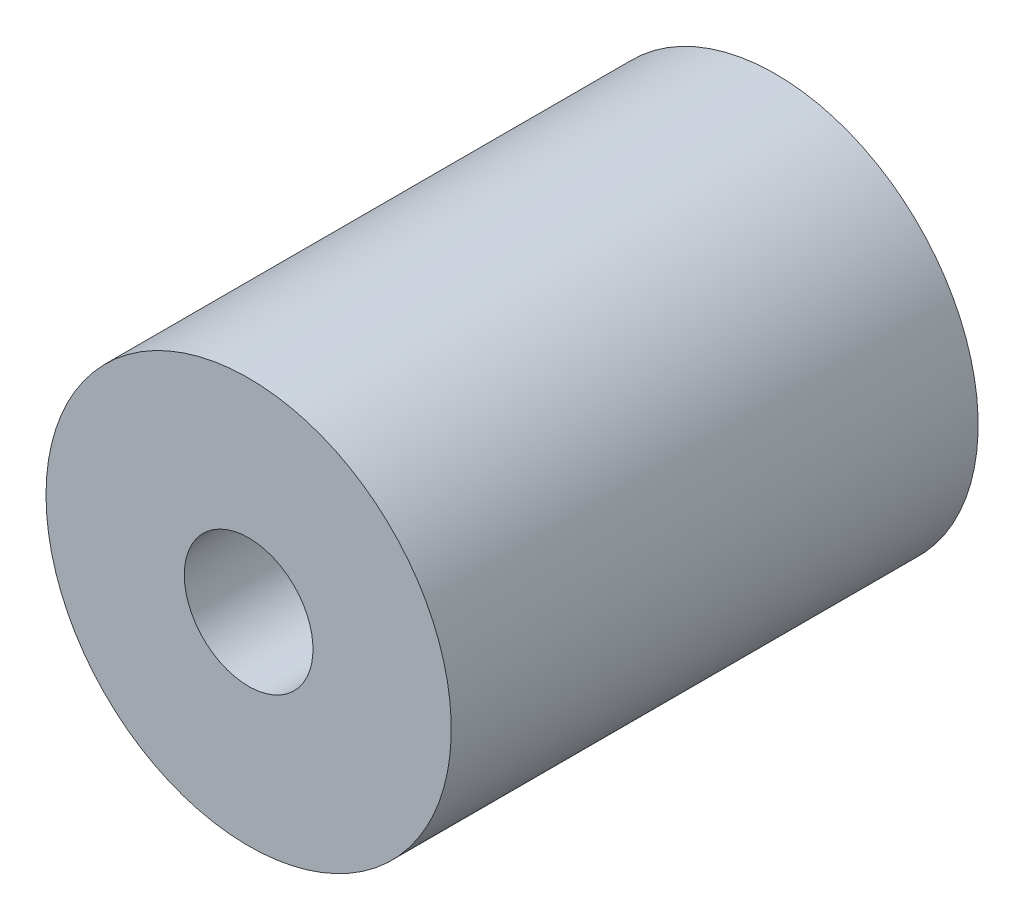
SolidWorks part; units mm, degrees
material "SKD11淬火HRC56-60"
ref_plane "前基準面" through (0, 0, 0) normal (0, 0, 1) x (1, 0, 0)
ref_plane "上基準面" through (0, 0, 0) normal (0, 1, 0) x (1, 0, 0)
ref_plane "右基準面" through (0, 0, 0) normal (1, 0, 0) x (0, 0, -1)
sketch "草图1" plane through (0, 0, 0) normal (0, 0, 1) x (1, 0, 0)
  circle A0 centre (0, 0) radius 10
  circle A1 centre (0, 0) radius 3.175
  dimension "D1" = 6.35
  dimension "D2" = 20
extrude "凸台-拉伸1" add sketch "草图1" along normal blind 26
sketch "草图3" plane through (0, 0, 0) normal (0, 0, -1) x (-1, 0, 0)
  circle A0 centre (0, 0) radius 4
  dimension "D1" = 8
extrude "切除-拉伸1" cut sketch "草图3" against normal blind 6.5
